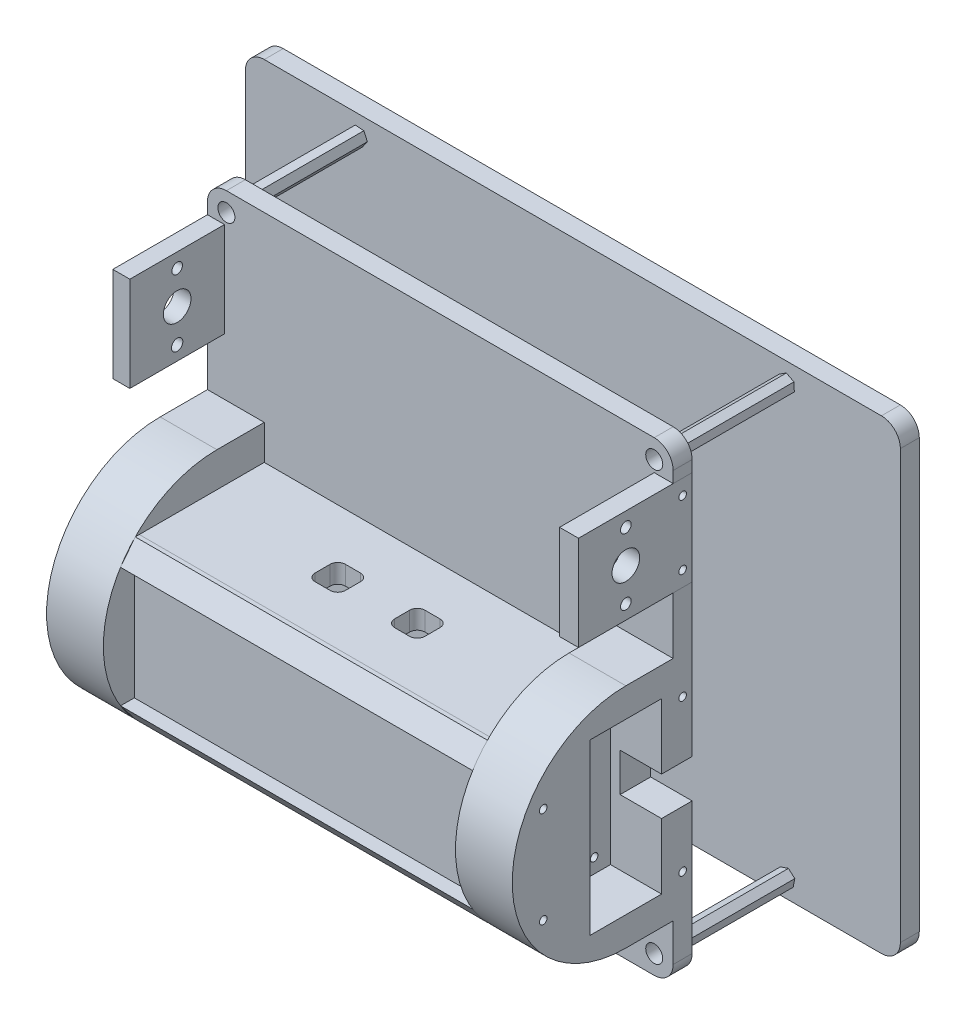
SolidWorks part; units mm, degrees
ref_plane "Plano frontal" through (0, 0, 0) normal (0, 0, 1) x (1, 0, 0)
ref_plane "Plano superior" through (0, 0, 0) normal (0, 1, 0) x (1, 0, 0)
ref_plane "Plano direito" through (0, 0, 0) normal (1, 0, 0) x (0, 0, -1)
sketch "Esboço1" plane through (0, 0, 0) normal (0, 0, 1) x (1, 0, 0)
  line L1 (-47.8109, 58.4855) -> (65.1891, 58.4855)
  line L2 (-52.8109, 53.4855) -> (-52.8109, -59.5145)
  line L3 (-47.8109, -64.5145) -> (65.1891, -64.5145)
  line L4 (70.1891, 53.4855) -> (70.1891, -59.5145)
  arc A0 (70.1891, 53.4855) -> (65.1891, 58.4855) centre (65.1891, 53.4855) ccw
  arc A1 (70.1891, -59.5145) -> (65.1891, -64.5145) centre (65.1891, -59.5145) cw
  arc A2 (-52.8109, -59.5145) -> (-47.8109, -64.5145) centre (-47.8109, -59.5145) ccw
  arc A3 (-52.8109, 53.4855) -> (-47.8109, 58.4855) centre (-47.8109, 53.4855) cw
  dimension "D1" = 5
extrude "Ressalto-extrusão1" add sketch "Esboço1" along normal blind 5
sketch "Esboço4" plane through (0, 0, 5) normal (0, 0, 1) x (1, 0, 0)
  line L0 (-52.8109, 53.4855) -> (-52.8109, -59.5145) construction
  line L1 (-52.8109, 50.4855) -> (-48.3154, 50.4855)
  line L2 (-52.8109, 50.4855) -> (-52.8109, 25.4855)
  line L3 (-52.8109, 25.4855) -> (-48.3154, 25.4855)
  line L4 (-48.3154, 50.4855) -> (-48.3154, 25.4855)
  line L5 (65.1891, 58.4855) -> (-47.8109, 58.4855) construction
  dimension "D1" = 8
extrude "Corte-extrusão2" cut sketch "Esboço4" against normal blind 5
sketch "Esboço5" plane through (0, 0, 5) normal (0, 0, 1) x (1, 0, 0)
  line L1 (-52.8109, 50.4855) -> (-48.3154, 50.4855)
  line L2 (-52.8109, 50.4855) -> (-52.8109, 25.4855)
  line L3 (-52.8109, 25.4855) -> (-48.3154, 25.4855)
  line L4 (-48.3154, 50.4855) -> (-48.3154, 25.4855)
extrude "Ressalto-extrusão2" add sketch "Esboço5" along normal blind 25 and the other way blind 5 separate body
sketch "Esboço6" plane through (-52.8109, 0, 0) normal (-1, 0, 0) x (0, 0, 1)
  line L0 (0, 50.4855) -> (5, 50.4855) construction
  line L1 (0, 50.4855) -> (0, 25.4855) construction
  circle A0 centre (2.5, 46.4855) radius 1
  point P4 (2.5, 50.4855)
  dimension "D1" = 4
  dimension "D2" = 2.5
extrude "Corte-extrusão3" cut sketch "Esboço6" against normal blind 10
sketch "Esboço7" plane through (-52.8109, 0, 0) normal (-1, 0, 0) x (0, 0, 1)
  line L0 (0, 25.4855) -> (5, 25.4855) construction
  line L1 (0, 50.4855) -> (0, 25.4855) construction
  circle A0 centre (2.5, 29.4855) radius 1
  point P4 (2.5, 25.4855)
  dimension "D1" = 4
  dimension "D2" = 2.5
extrude "Corte-extrusão4" cut sketch "Esboço7" against normal blind 10
sketch "Esboço8" plane through (-48.3154, 0, 0) normal (1, 0, 0) x (0, 0, -1)
  line L0 (0, 50.4855) -> (-30, 50.4855) construction
  line L1 (-30, 25.4855) -> (-30, 50.4855) construction
  circle A0 centre (-17.5, 37.9855) radius 3.65
  dimension "D1" = 12.5
  dimension "D2" = 12.5
extrude "Corte-extrusão5" cut sketch "Esboço8" against normal blind 10
sketch "Esboço9" plane through (-52.8109, 0, 0) normal (-1, 0, 0) x (0, 0, 1)
  line L1 (30, 50.4855) -> (30, 25.4855) construction
  circle A0 centre (17.5, 46.7355) radius 1.4
  circle A1 centre (17.5, 37.9855) radius 3.65 construction
  dimension "D1" = 8.75
  dimension "D2" = 12.5
extrude "Corte-extrusão6" cut sketch "Esboço9" against normal blind 10
sketch "Esboço10" plane through (-52.8109, 0, 0) normal (-1, 0, 0) x (0, 0, 1)
  line L0 (30, 50.4855) -> (30, 25.4855) construction
  circle A0 centre (17.5, 29.2355) radius 1.5
  circle A1 centre (17.5, 37.9855) radius 3.65 construction
  dimension "D1" = 8.75
  dimension "D2" = 12.5
extrude "Corte-extrusão7" cut sketch "Esboço10" against normal blind 10
sketch "Esboço11" plane through (0, 0, 5) normal (0, 0, 1) x (1, 0, 0)
  line L0 (70.1891, -59.5145) -> (70.1891, 53.4855) construction
  line L1 (70.1891, 50.4855) -> (65.1891, 50.4855)
  line L2 (70.1891, 50.4855) -> (70.1891, 25.4855)
  line L3 (70.1891, 25.4855) -> (65.1891, 25.4855)
  line L4 (65.1891, 50.4855) -> (65.1891, 25.4855)
  line L5 (65.1891, 58.4855) -> (-47.8109, 58.4855) construction
  dimension "D1" = 8
extrude "Corte-extrusão8" cut sketch "Esboço11" against normal blind 10
sketch "Esboço16" plane through (0, 0, 5) normal (0, 0, 1) x (1, 0, 0)
  line L1 (65.1891, 50.4855) -> (70.1891, 50.4855)
  line L2 (65.1891, 50.4855) -> (65.1891, 25.4855)
  line L3 (65.1891, 25.4855) -> (70.1891, 25.4855)
  line L4 (70.1891, 50.4855) -> (70.1891, 25.4855)
extrude "Ressalto-extrusão3" add sketch "Esboço16" along normal blind 25 and the other way blind 5 separate body
sketch "Esboço17" plane through (70.1891, 0, 0) normal (1, 0, 0) x (0, 0, -1)
  line L0 (0, 50.4855) -> (-5, 50.4855) construction
  line L1 (0, 25.4855) -> (0, 50.4855) construction
  circle A0 centre (-2.5, 46.4855) radius 1
  dimension "D1" = 4
  dimension "D2" = 2.5
extrude "Corte-extrusão9" cut sketch "Esboço17" against normal blind 10
sketch "Esboço18" plane through (70.1891, 0, 0) normal (1, 0, 0) x (0, 0, -1)
  line L0 (0, 25.4855) -> (-30, 25.4855) construction
  line L1 (0, 25.4855) -> (0, 50.4855) construction
  circle A0 centre (-2.5, 29.4855) radius 1
  dimension "D1" = 4
  dimension "D2" = 2.5
extrude "Corte-extrusão10" cut sketch "Esboço18" against normal blind 10
sketch "Esboço20" plane through (70.1891, 0, 0) normal (1, 0, 0) x (0, 0, -1)
  line L0 (-30, 25.4855) -> (-30, 50.4855) construction
  line L1 (0, 50.4855) -> (-30, 50.4855) construction
  circle A0 centre (-17.5, 37.9855) radius 3.65
  dimension "D1" = 12.5
  dimension "D2" = 12.5
extrude "Corte-extrusão11" cut sketch "Esboço20" against normal blind 6
sketch "Esboço22" plane through (70.1891, 0, 0) normal (1, 0, 0) x (0, 0, -1)
  line L1 (-30, 25.4855) -> (-30, 50.4855) construction
  circle A0 centre (-17.5, 46.7355) radius 1.4
  circle A1 centre (-17.5, 37.9855) radius 3.65 construction
  dimension "D1" = 8.75
  dimension "D2" = 12.5
extrude "Corte-extrusão12" cut sketch "Esboço22" against normal blind 5
sketch "Esboço23" plane through (70.1891, 0, 0) normal (1, 0, 0) x (0, 0, -1)
  line L0 (-30, 25.4855) -> (-30, 50.4855) construction
  circle A0 centre (-17.5, 29.2355) radius 1.4
  circle A1 centre (-17.5, 37.9855) radius 3.65 construction
  dimension "D1" = 12.5
  dimension "D2" = 8.75
extrude "Corte-extrusão13" cut sketch "Esboço23" against normal blind 5
sketch "Esboço24" plane through (0, 0, 5) normal (0, 0, 1) x (1, 0, 0)
  line L0 (-52.8109, 25.4855) -> (-52.8109, -59.5145) construction
  line L1 (-52.8109, -49.5145) -> (-37.8109, -49.5145)
  line L2 (-52.8109, -49.5145) -> (-52.8109, 10.4855)
  line L3 (-52.8109, 10.4855) -> (-37.8109, 10.4855)
  line L4 (-37.8109, -49.5145) -> (-37.8109, 10.4855)
  line L6 (-47.8109, -64.5145) -> (65.1891, -64.5145) construction
  dimension "D1" = 15
extrude "Corte-extrusão14" cut sketch "Esboço24" against normal blind 10
sketch "Esboço27" plane through (0, 0, 5) normal (0, 0, 1) x (1, 0, 0)
  line L0 (70.1891, -59.5145) -> (70.1891, 25.4855) construction
  line L1 (70.1891, -49.5145) -> (55.1891, -49.5145)
  line L2 (70.1891, -49.5145) -> (70.1891, 10.4855)
  line L3 (70.1891, 10.4855) -> (55.1891, 10.4855)
  line L4 (55.1891, -49.5145) -> (55.1891, 10.4855)
  line L5 (-52.8109, -49.5145) -> (-37.8109, -49.5145) construction
  line L6 (-47.8109, -64.5145) -> (65.1891, -64.5145) construction
  dimension "D1" = 15
  dimension "D2" = 15
extrude "Corte-extrusão16" cut sketch "Esboço27" against normal blind 25
sketch "Esboço32" plane through (0, 0, 5) normal (0, 0, 1) x (1, 0, 0)
  line L1 (-52.8109, 10.4855) -> (-37.8109, 10.4855)
  line L2 (-52.8109, 10.4855) -> (-52.8109, -49.5145)
  line L3 (-52.8109, -49.5145) -> (-37.8109, -49.5145)
  line L4 (-37.8109, 10.4855) -> (-37.8109, -49.5145)
extrude "Ressalto-extrusão7" add sketch "Esboço32" along normal blind 12.5 and the other way blind 5 separate body
sketch "Esboço33" plane through (-52.8109, 0, 0) normal (-1, 0, 0) x (0, 0, 1)
  line L4 (0, -49.5145) -> (17.5, -49.5145)
  line L5 (17.5, -49.5145) -> (17.5, 10.4855)
  line L6 (17.5, 10.4855) -> (0, 10.4855)
  line L7 (0, 10.4855) -> (0, -49.5145)
  line L8 (0, -49.5145) -> (17.5, -49.5145)
  line L10 (17.5, 10.4855) -> (0, 10.4855)
  line L11 (0, 10.4855) -> (0, -49.5145)
  arc A0 (17.5, 10.4855) -> (17.5, -49.5145) centre (17.5, -19.5145) cw
  dimension "D1" = 0
extrude "Ressalto-extrusão8" add sketch "Esboço33" against normal blind 15 separate body
sketch "Esboço34" plane through (0, 0, 5) normal (0, 0, 1) x (1, 0, 0)
  line L1 (55.1891, 10.4855) -> (70.1891, 10.4855)
  line L2 (55.1891, 10.4855) -> (55.1891, -49.5145)
  line L3 (55.1891, -49.5145) -> (70.1891, -49.5145)
  line L4 (70.1891, 10.4855) -> (70.1891, -49.5145)
extrude "Ressalto-extrusão9" add sketch "Esboço34" along normal blind 12.5 and the other way blind 5 separate body
sketch "Esboço35" plane through (70.1891, 0, 0) normal (1, 0, 0) x (0, 0, -1)
  line L4 (0, 10.4855) -> (-17.5, 10.4855)
  line L5 (-17.5, 10.4855) -> (-17.5, -49.5145)
  line L6 (-17.5, -49.5145) -> (0, -49.5145)
  line L7 (0, -49.5145) -> (0, 10.4855)
  line L8 (0, 10.4855) -> (-17.5, 10.4855)
  line L10 (-17.5, -49.5145) -> (0, -49.5145)
  line L11 (0, -49.5145) -> (0, 10.4855)
  arc A0 (-17.5, -49.5145) -> (-17.5, 10.4855) centre (-17.5, -19.5145) cw
  dimension "D1" = 0
extrude "Ressalto-extrusão10" add sketch "Esboço35" against normal blind 15 separate body
sketch "Esboço36" plane through (70.1891, 0, 0) normal (1, 0, 0) x (0, 0, -1)
  line L0 (-17.5, -49.5145) -> (0, -49.5145) construction
  line L1 (0, -49.5145) -> (0, 10.4855) construction
  circle A0 centre (-2.5, -39.5145) radius 1
  circle A2 centre (-2.5, 0.4855) radius 1
  dimension "D1" = 10
  dimension "D2" = 2.5
  dimension "D5" = 2.5
  dimension "D6" = 50
extrude "Corte-extrusão18" cut sketch "Esboço36" against normal blind 20
sketch "Esboço37" plane through (-52.8109, 0, 0) normal (-1, 0, 0) x (0, 0, 1)
  line L0 (0, 10.4855) -> (5, 10.4855) construction
  line L1 (0, 10.4855) -> (0, -49.5145) construction
  circle A0 centre (2.5, 0.4855) radius 1
  circle A2 centre (2.5, -39.5145) radius 1
  dimension "D1" = 10
  dimension "D2" = 2.5
  dimension "D5" = 50
  dimension "D6" = 2.5
extrude "Corte-extrusão19" cut sketch "Esboço37" against normal blind 20
sketch "Esboço39" plane through (70.1891, 0, 0) normal (1, 0, 0) x (0, 0, -1)
  line L1 (-26.9163, -41.876) -> (-8.0663, -41.876)
  line L2 (-26.9163, -41.876) -> (-26.9163, 2.829)
  line L3 (-26.9163, 2.829) -> (-8.0663, 2.829)
  line L4 (-8.0663, -41.876) -> (-8.0663, 2.829)
extrude "Corte-extrusão20" cut sketch "Esboço39" against normal blind 13.49
sketch "Esboço41" plane through (56.6991, 0, 0) normal (1, 0, 0) x (0, 0, -1)
  line L0 (-8.0663, 2.829) -> (-26.9163, 2.829) construction
  line L1 (-26.9163, 2.829) -> (-26.9163, -41.876) construction
  circle A0 centre (-20.3753, -0.981) radius 1.6255
  circle A1 centre (-12.3753, -0.981) radius 1
  dimension "D1" = 3.81
  dimension "D2" = 6.541
  dimension "D3" = 8
sketch "Esboço42" plane through (56.6991, 0, 0) normal (1, 0, 0) x (0, 0, -1)
  line L0 (-26.9163, 2.829) -> (-26.9163, -41.876) construction
  line L1 (-26.9163, -41.876) -> (-8.0663, -41.876) construction
  circle A0 centre (-20.3753, -38.066) radius 1.6255
  circle A1 centre (-12.3753, -38.066) radius 1
  dimension "D1" = 6.541
  dimension "D3" = 8
  dimension "D2" = 3.81
sketch "Esboço43" plane through (0, 0, 8.0663) normal (0, 0, 1) x (1, 0, 0)
  line L1 (59.2391, -24.5945) -> (70.1891, -24.5945)
  line L2 (59.2391, -24.5945) -> (59.2391, -14.4345)
  line L3 (59.2391, -14.4345) -> (70.1891, -14.4345)
  line L4 (70.1891, -24.5945) -> (70.1891, -14.4345)
  line L6 (56.6991, -41.876) -> (56.6991, 2.829) construction
  line L7 (55.1891, -49.5145) -> (70.1891, -49.5145) construction
  line L8 (70.1891, 10.4855) -> (55.1891, 10.4855) construction
  line L9 (70.1891, -41.876) -> (70.1891, 2.829) construction
  point P8 (64.7141, -14.4345)
  dimension "D1" = 2.54
  dimension "D2" = 24.92
  dimension "D3" = 24.92
extrude "Corte-extrusão23" cut sketch "Esboço43" against normal blind 10
sketch "Esboço44" plane through (55.1891, 0, 0) normal (-1, 0, 0) x (0, 0, 1)
  line L0 (5, 10.4855) -> (5, -49.5145) construction
  line L1 (38, 1.3305) -> (5, 1.3305)
  line L2 (38, 1.3305) -> (38, -3.6695)
  line L3 (38, -3.6695) -> (5, -3.6695)
  line L4 (5, 1.3305) -> (5, -3.6695)
extrude "Ressalto-extrusão11" add sketch "Esboço44" along normal blind 93 separate body
sketch "Esboço47" plane through (55.1891, 0, 0) normal (-1, 0, 0) x (0, 0, 1)
  line L0 (5, 10.4855) -> (5, -49.5145) construction
  line L1 (5, -35.3645) -> (38, -35.3645)
  line L2 (5, -35.3645) -> (5, -40.3645)
  line L3 (5, -40.3645) -> (38, -40.3645)
  line L4 (38, -35.3645) -> (38, -40.3645)
  line L5 (38, 1.3305) -> (5, 1.3305) construction
  line L6 (0, 10.4855) -> (17.5, 10.4855) construction
  line L7 (17.5, -49.5145) -> (0, -49.5145) construction
  dimension "D1" = 9.155
  dimension "D2" = 9.15
extrude "Ressalto-extrusão12" add sketch "Esboço47" along normal blind 93
extrude "Corte-extrusão25" cut sketch "Esboço41" against normal blind 31
extrude "Corte-extrusão26" cut sketch "Esboço42" against normal blind 31
sketch "Esboço52" plane through (-52.8109, 0, 0) normal (-1, 0, 0) x (0, 0, 1)
  line L1 (29.6732, 2.8455) -> (10.8232, 2.8455)
  line L2 (29.6732, 2.8455) -> (29.6732, -41.8595)
  line L3 (29.6732, -41.8595) -> (10.8232, -41.8595)
  line L4 (10.8232, 2.8455) -> (10.8232, -41.8595)
  line L7 (5, 10.4855) -> (17.5, 10.4855) construction
  point P15 (11.25, 10.4855)
  dimension "D2" = 7.64
extrude "Corte-extrusão27" cut sketch "Esboço52" against normal blind 13.49
sketch "Esboço54" plane through (0, 0, 10.8232) normal (0, 0, 1) x (1, 0, 0)
  line L0 (-52.8109, 2.8455) -> (-52.8109, -41.8595) construction
  line L1 (-52.8109, -14.4345) -> (-41.8599, -14.4345)
  line L2 (-52.8109, -14.4345) -> (-52.8109, -24.5945)
  line L3 (-52.8109, -24.5945) -> (-41.8599, -24.5945)
  line L4 (-41.8599, -14.4345) -> (-41.8599, -24.5945)
  line L5 (-52.8109, -49.5145) -> (-37.8109, -49.5145) construction
  line L6 (-37.8109, 10.4855) -> (-52.8109, 10.4855) construction
  dimension "D1" = 24.92
  dimension "D2" = 24.92
extrude "Corte-extrusão28" cut sketch "Esboço54" against normal blind 24
sketch "Esboço55" plane through (-39.3209, 0, 0) normal (-1, 0, 0) x (0, 0, 1)
  line L0 (29.6732, -41.8595) -> (29.6732, 2.8455) construction
  line L1 (29.6732, 2.8455) -> (10.8232, 2.8455) construction
  line L2 (10.8232, -41.8595) -> (29.6732, -41.8595) construction
  line L3 (29.6732, -41.8595) -> (29.6732, 2.8455) construction
  circle A0 centre (23.1332, -0.9645) radius 1.6255
  circle A1 centre (23.1332, -38.0495) radius 1.6255
  circle A2 centre (15.1332, -0.9645) radius 1
  circle A3 centre (15.1332, -38.0495) radius 1
  dimension "D1" = 6.54
  dimension "D3" = 3.81
  dimension "D5" = 8
  dimension "D2" = 3.81
  dimension "D4" = 6.54
extrude "Corte-extrusão29" cut sketch "Esboço55" against normal blind 31
sketch "Esboço56" plane through (55.1891, 0, 0) normal (-1, 0, 0) x (0, 0, 1)
  line L0 (5, -3.6695) -> (38, -3.6695) construction
  line L1 (39.32, -3.6695) -> (34.32, -3.6695)
  line L2 (39.32, -3.6695) -> (39.32, -35.3645)
  line L3 (39.32, -35.3645) -> (34.32, -35.3645)
  line L4 (34.32, -3.6695) -> (34.32, -35.3645)
  line L5 (38, -35.3645) -> (5, -35.3645) construction
  arc A0 (17.5, -49.5145) -> (17.5, 10.4855) centre (17.5, -19.5145) ccw construction
  point P11 (47.5, -19.5145)
  dimension "D1" = 8.18
extrude "Ressalto-extrusão13" add sketch "Esboço56" along normal blind 93
sketch "Esboço59" plane through (55.1891, 0, 0) normal (-1, 0, 0) x (0, 0, 1)
  line L0 (38, 1.3305) -> (38, -3.6695)
  line L1 (38, -3.6695) -> (42.9742, -3.6695)
  line L2 (42.9742, -3.6695) -> (39.0751, 1.3305)
  line L3 (39.0751, 1.3305) -> (38, 1.3305)
  arc A0 (17.5, -49.5145) -> (17.5, 10.4855) centre (17.5, -19.5145) ccw construction
extrude "Ressalto-extrusão15" add sketch "Esboço59" along normal blind 93 separate body
sketch "Esboço61" plane through (55.1891, 0, 0) normal (-1, 0, 0) x (0, 0, 1)
  line L0 (38, -40.3645) -> (38, -35.3645)
  line L1 (38, -35.3645) -> (42.9711, -35.3645)
  line L2 (42.9711, -35.3645) -> (39.0703, -40.3645)
  line L3 (38, -40.3645) -> (39.0703, -40.3645)
  arc A0 (17.5, -49.5145) -> (17.5, 10.4855) centre (17.5, -19.5145) ccw construction
extrude "Ressalto-extrusão16" add sketch "Esboço61" along normal blind 93 separate body
sketch "Esboço62" plane through (70.1891, 0, 0) normal (1, 0, 0) x (0, 0, -1)
  circle A2 centre (-39.32, -32.23) radius 1
  circle A4 centre (-39.32, -6.7995) radius 1
  dimension "D2" = 8.13
extrude "Corte-extrusão30" cut sketch "Esboço62" against normal blind 14 contours A2 | A4
sketch "Esboço64" plane through (0, 1.3305, 0) normal (0, 1, 0) x (1, 0, 0)
  line L0 (55.1891, -38) -> (55.1891, -5) construction
  line L1 (21.1891, -25.5878) -> (17.1891, -25.5878)
  line L2 (23.1891, -23.5878) -> (23.1891, -19.5878)
  line L3 (21.1891, -17.5878) -> (17.1891, -17.5878)
  line L4 (15.1891, -23.5878) -> (15.1891, -19.5878)
  line L5 (0.1891, -25.5878) -> (-3.8109, -25.5878)
  line L6 (2.1891, -23.5878) -> (2.1891, -19.5878)
  line L7 (0.1891, -17.5878) -> (-3.8109, -17.5878)
  line L8 (-5.8109, -23.5878) -> (-5.8109, -19.5878)
  line L9 (-37.8109, -38) -> (-37.8109, -5) construction
  arc A0 (15.1891, -23.5878) -> (17.1891, -25.5878) centre (17.1891, -23.5878) ccw
  arc A1 (15.1891, -19.5878) -> (17.1891, -17.5878) centre (17.1891, -19.5878) cw
  arc A2 (0.1891, -17.5878) -> (2.1891, -19.5878) centre (0.1891, -19.5878) cw
  arc A3 (0.1891, -25.5878) -> (2.1891, -23.5878) centre (0.1891, -23.5878) ccw
  arc A4 (-5.8109, -23.5878) -> (-3.8109, -25.5878) centre (-3.8109, -23.5878) ccw
  arc A5 (-5.8109, -19.5878) -> (-3.8109, -17.5878) centre (-3.8109, -19.5878) cw
  arc A6 (21.1891, -17.5878) -> (23.1891, -19.5878) centre (21.1891, -19.5878) cw
  arc A7 (23.1891, -23.5878) -> (21.1891, -25.5878) centre (21.1891, -23.5878) cw
  point P22 (-5.8109, -25.5878)
  dimension "D3" = 2
  dimension "D1" = 32
  dimension "D2" = 32
extrude "Corte-extrusão31" cut sketch "Esboço64" against normal blind 10 contours L4 A1 L3 A6 L2 A7 L1 A0 | L8 A5 L7 A2 L6 A3 L5 A4
sketch "Esboço65" plane through (0, 0, 0) normal (0, 0, -1) x (-1, 0, 0)
  line L0 (47.8109, -64.5145) -> (-65.1891, -64.5145) construction
  line L1 (52.8109, -24.5945) -> (52.8109, -59.5145) construction
  line L2 (-65.1891, 58.4855) -> (47.8109, 58.4855) construction
  line L3 (52.8109, 53.4855) -> (52.8109, 50.4855) construction
  line L4 (-70.1891, 50.4855) -> (-70.1891, 53.4855) construction
  circle A0 centre (47.8109, -59.5145) radius 2.25
  circle A1 centre (47.8109, 53.4855) radius 2.25
  circle A2 centre (-65.1891, 53.4855) radius 2.25
  circle A3 centre (-65.1891, -59.5145) radius 2.25
  dimension "D1" = 5
  dimension "D3" = 5
  dimension "D5" = 5
  dimension "D6" = 5
  dimension "D2" = 5
  dimension "D4" = 5
extrude "Corte-extrusão32" cut sketch "Esboço65" against normal blind 10
sketch "Esboço66" plane through (0, 0, 0) normal (0, 0, -1) x (-1, 0, 0)
  line L1 (45.6793, -58.7943) -> (46.1214, -61.0004)
  line L2 (46.1214, -61.0004) -> (48.253, -61.7206)
  line L3 (48.253, -61.7206) -> (49.9425, -60.2347)
  line L4 (49.9425, -60.2347) -> (49.5005, -58.0286)
  line L5 (49.5005, -58.0286) -> (47.3689, -57.3084)
  line L6 (47.3689, -57.3084) -> (45.6793, -58.7943)
  line L7 (-67.3207, -58.7943) -> (-66.8786, -61.0004)
  line L8 (-66.8786, -61.0004) -> (-64.747, -61.7206)
  line L9 (-64.747, -61.7206) -> (-63.0575, -60.2347)
  line L10 (-63.0575, -60.2347) -> (-63.4995, -58.0286)
  line L11 (-63.4995, -58.0286) -> (-65.6311, -57.3084)
  line L12 (-65.6311, -57.3084) -> (-67.3207, -58.7943)
  line L13 (-67.0855, 54.6963) -> (-67.1859, 52.4486)
  line L14 (-67.1859, 52.4486) -> (-65.2895, 51.2377)
  line L15 (-65.2895, 51.2377) -> (-63.2926, 52.2747)
  line L16 (-63.2926, 52.2747) -> (-63.1923, 54.5225)
  line L17 (-63.1923, 54.5225) -> (-65.0887, 55.7333)
  line L18 (-65.0887, 55.7333) -> (-67.0855, 54.6963)
  line L19 (46.5241, 55.3312) -> (45.5691, 53.2939)
  line L20 (45.5691, 53.2939) -> (46.8559, 51.4482)
  line L21 (46.8559, 51.4482) -> (49.0978, 51.6398)
  line L22 (49.0978, 51.6398) -> (50.0528, 53.6771)
  line L23 (50.0528, 53.6771) -> (48.7659, 55.5228)
  line L24 (48.7659, 55.5228) -> (46.5241, 55.3312)
  circle A0 centre (47.8109, -59.5145) radius 1.9486 construction
  circle A1 centre (-65.1891, -59.5145) radius 1.9486 construction
  circle A2 centre (-65.1891, 53.4855) radius 1.9486 construction
  circle A3 centre (47.8109, 53.4855) radius 1.9486 construction
extrude "Ressalto-extrusão17" add sketch "Esboço66" along normal blind 30 separate body
sketch "Esboço68" plane through (0, 0, -30) normal (0, 0, -1) x (-1, 0, 0)
  line L0 (-70.1891, -14.4345) -> (-70.1891, 25.4855) construction
  line L1 (-90.1891, 58.4855) -> (72.8109, 58.4855)
  line L2 (-95.1891, 53.4855) -> (-95.1891, -59.5145)
  line L3 (-90.1891, -64.5145) -> (72.8109, -64.5145)
  line L4 (77.8109, 53.4855) -> (77.8109, -59.5145)
  line L5 (52.8109, 25.4855) -> (52.8109, -14.4345) construction
  line L6 (-65.1891, 58.4855) -> (47.8109, 58.4855) construction
  line L7 (47.8109, -64.5145) -> (-65.1891, -64.5145) construction
  arc A0 (77.8109, 53.4855) -> (72.8109, 58.4855) centre (72.8109, 53.4855) ccw
  arc A1 (77.8109, -59.5145) -> (72.8109, -64.5145) centre (72.8109, -59.5145) cw
  arc A2 (-90.1891, -64.5145) -> (-95.1891, -59.5145) centre (-90.1891, -59.5145) cw
  arc A3 (-90.1891, 58.4855) -> (-95.1891, 53.4855) centre (-90.1891, 53.4855) ccw
  dimension "D5" = 5
  dimension "D1" = 123
  dimension "D2" = 0
  dimension "D3" = 25
  dimension "D4" = 25
extrude "Ressalto-extrusão18" add sketch "Esboço68" along normal blind 5 separate body
sketch "Esboço69" plane through (0, -40.3645, 0) normal (0, -1, 0) x (1, 0, 0)
  line L0 (-37.8109, 5) -> (-37.8109, 38) construction
  line L1 (-37.8109, 5) -> (55.1891, 5) construction
  circle A0 centre (-9.8534, 27) radius 1.6255
  dimension "D1" = 27.9575
  dimension "D2" = 22
extrude "Corte-extrusão33" cut sketch "Esboço69" against normal blind 10
sketch "Esboço71" plane through (0, -40.3645, 0) normal (0, -1, 0) x (1, 0, 0)
  line L0 (-47.8109, 5) -> (65.1891, 5) construction
  line L1 (55.1891, 5) -> (55.1891, 38) construction
  circle A0 centre (27.2316, 27) radius 1.6255
  dimension "D1" = 22
  dimension "D2" = 27.9575
extrude "Corte-extrusão34" cut sketch "Esboço71" against normal blind 10
